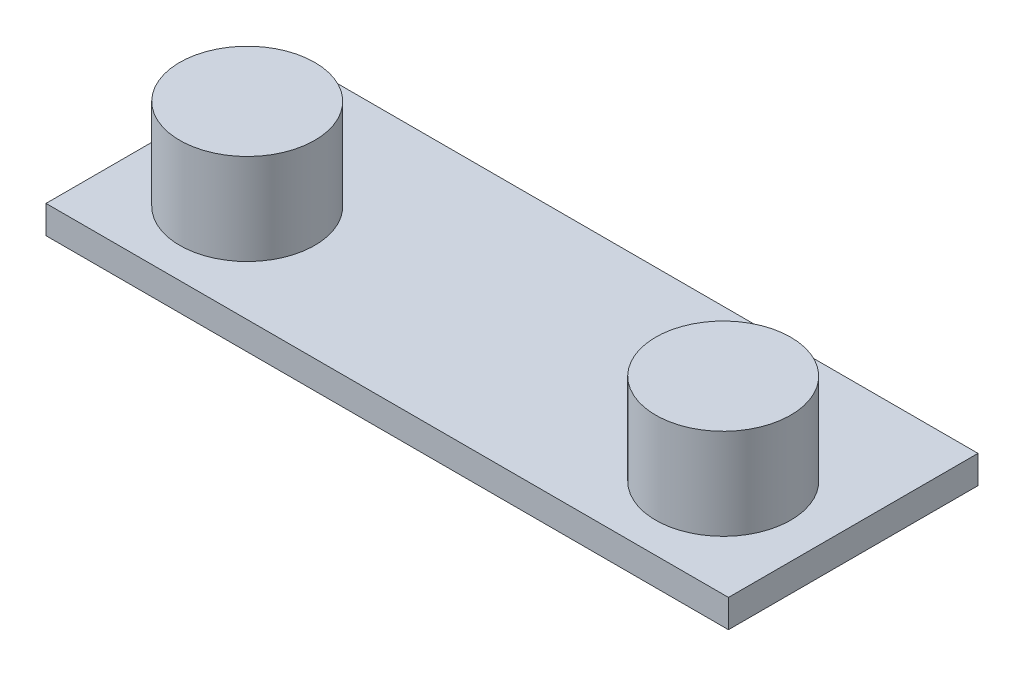
SolidWorks part; units mm, degrees
ref_plane "前视基准面" through (0, 0, 0) normal (0, 0, 1) x (1, 0, 0)
ref_plane "上视基准面" through (0, 0, 0) normal (0, 1, 0) x (1, 0, 0)
ref_plane "右视基准面" through (0, 0, 0) normal (1, 0, 0) x (0, 0, -1)
other "质心 (COM)"
sketch "草图1" plane through (0, 0, 0) normal (0, 1, 0) x (1, 0, 0)
  line L1 (97.5, -35.65) -> (-97.5, -35.65)
  line L2 (97.5, -35.65) -> (97.5, 35.65)
  line L3 (97.5, 35.65) -> (-97.5, 35.65)
  line L4 (-97.5, -35.65) -> (-97.5, 35.65)
  line L5 (97.5, -35.65) -> (-97.5, 35.65) construction
  line L6 (97.5, 35.65) -> (-97.5, -35.65) construction
  point P0 (0, 0)
  dimension "D1" = 71.3
  dimension "D2" = 195
extrude "凸台-拉伸1" add sketch "草图1" along normal blind 8
sketch "草图2" plane through (0, 8, 0) normal (0, 1, 0) x (1, 0, 0)
  line L4 (-97.5, 35.65) -> (-97.5, -35.65)
  line L5 (-97.5, -35.65) -> (97.5, -35.65)
  line L6 (97.5, -35.65) -> (97.5, 35.65)
  line L7 (97.5, 35.65) -> (-97.5, 35.65)
  line L8 (-97.5, 35.65) -> (-97.5, -35.65) construction
  line L9 (-97.5, -35.65) -> (97.5, -35.65) construction
  line L10 (97.5, -35.65) -> (97.5, 35.65) construction
  line L11 (97.5, 35.65) -> (-97.5, 35.65) construction
  circle A0 centre (68, -7.65) radius 19.3
  circle A1 centre (-68, -7.65) radius 19.3
  dimension "D2" = 38.6
  dimension "D3" = 29.5
  dimension "D4" = 28
  dimension "D5" = 29.5
  dimension "D6" = 28
  dimension "D1" = 0
extrude "凸台-拉伸2" add sketch "草图2" along normal blind 26
